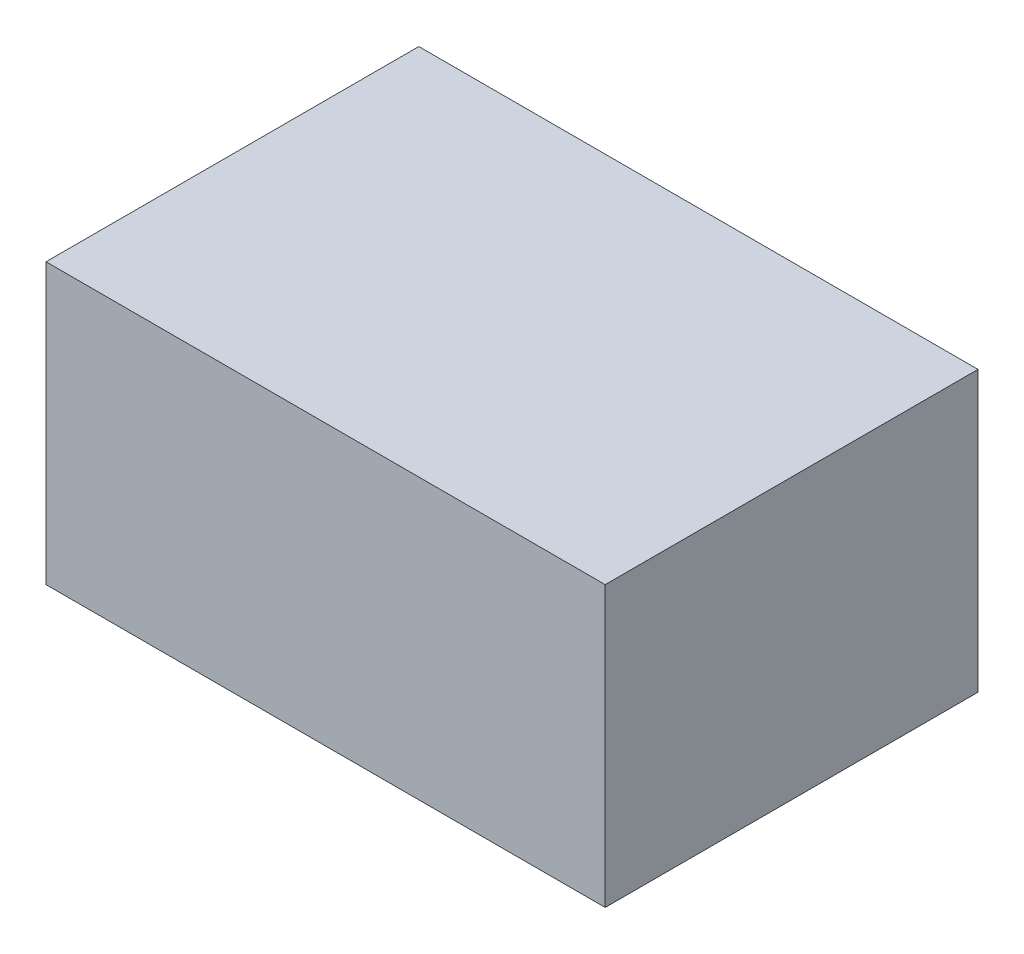
SolidWorks part; units mm, degrees
ref_plane "Front Plane" through (0, 0, 0) normal (0, 0, 1) x (1, 0, 0)
ref_plane "Top Plane" through (0, 0, 0) normal (0, 1, 0) x (1, 0, 0)
ref_plane "Right Plane" through (0, 0, 0) normal (1, 0, 0) x (0, 0, -1)
sketch "Sketch1" plane through (0, 0, 0) normal (0, 1, 0) x (1, 0, 0)
  line L1 (-118.9858, 62.8906) -> (181.0142, 62.8906)
  line L2 (-118.9858, 62.8906) -> (-118.9858, -137.1094)
  line L3 (-118.9858, -137.1094) -> (181.0142, -137.1094)
  line L4 (181.0142, 62.8906) -> (181.0142, -137.1094)
  dimension "D1" = 300
  dimension "D2" = 200
extrude "Boss-Extrude1" add sketch "Sketch1" along normal blind 150
